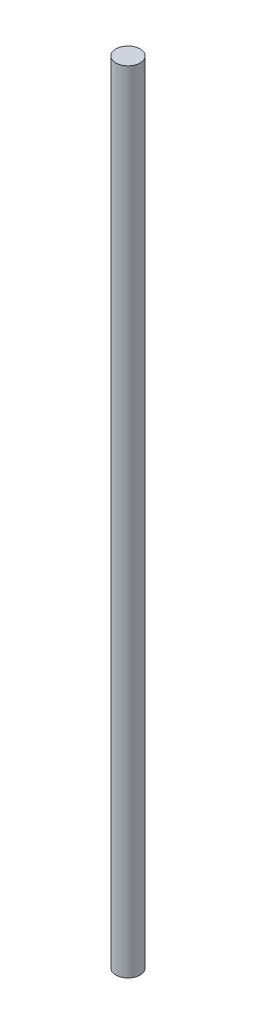
SolidWorks part; units mm, degrees
ref_plane "Front Plane" through (0, 0, 0) normal (0, 0, 1) x (1, 0, 0)
ref_plane "Top Plane" through (0, 0, 0) normal (0, 1, 0) x (1, 0, 0)
ref_plane "Right Plane" through (0, 0, 0) normal (1, 0, 0) x (0, 0, -1)
sketch "Sketch1" plane through (0, 0, 0) normal (0, 1, 0) x (1, 0, 0)
  circle A0 centre (0, 0) radius 2
  dimension "D1" = 4
extrude "Boss-Extrude1" add sketch "Sketch1" along normal blind 130
